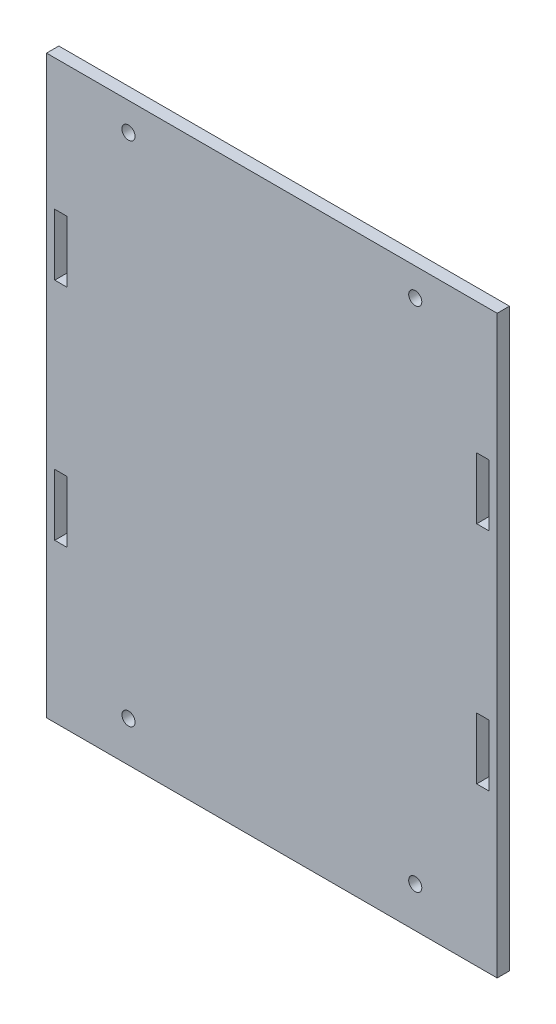
SolidWorks part; units mm, degrees
ref_plane "前视基准面" through (0, 0, 0) normal (0, 0, 1) x (1, 0, 0)
ref_plane "上视基准面" through (0, 0, 0) normal (0, 1, 0) x (1, 0, 0)
ref_plane "右视基准面" through (0, 0, 0) normal (1, 0, 0) x (0, 0, -1)
sketch "草图1" plane through (0, 0, 0) normal (0, 0, 1) x (1, 0, 0)
  line L0 (50, 124.6667) -> (50, -15.8667) construction
  line L1 (50, -15.8667) -> (178, -84.1333) construction
  line L2 (178, -84.1333) -> (294.7059, -5.8431) construction
  line L3 (294.7059, -5.8431) -> (50, 124.6667) construction
  line L4 (177.0588, -84.7647) -> (50, -17) construction
  line L5 (191.1765, -75.2941) -> (50, 0) construction
  line L6 (172.3529, 59.4118) -> (114, -50) construction
  line L7 (50, 124.6667) -> (-50, 124.6667)
  line L8 (50, -15.8667) -> (-50, -15.8667)
  line L9 (-50, -15.8667) -> (-50, 124.6667)
  line L10 (50, 124.6667) -> (50, -15.8667)
  line L11 (50, 0) -> (-50, 0) construction
  line L12 (-35, -6) -> (35, -6) construction
  line L13 (0, -6) -> (0, 0) construction
  line L14 (-35, 117.8667) -> (-50, 117.8667) construction
  line L15 (35, 117.8667) -> (50, 117.8667) construction
  circle A0 centre (-35, -6) radius 1.6
  circle A1 centre (35, -6) radius 1.6
  circle A2 centre (-35, 117.8667) radius 1.6
  circle A3 centre (35, 117.8667) radius 1.6
  point P9 (0, 0)
  dimension "D7" = 3.2
  dimension "D10" = 3.2
  dimension "D1" = 160
  dimension "D2" = 144
  dimension "D3" = 15
  dimension "D4" = 110
  dimension "D5" = 14
  dimension "D6" = 100
  dimension "D8" = 6
  dimension "D9" = 70
  dimension "D11" = 15
  dimension "D12" = 6
extrude "凸台-拉伸1" add sketch "草图1" against normal blind 3
sketch "草图2" plane through (0, 0, 0) normal (0, 0, 1) x (1, 0, 0)
  line L0 (-50, 124.6667) -> (-55, 124.6667)
  line L1 (-55, 124.6667) -> (-55, -15.8667)
  line L2 (-55, -15.8667) -> (-50, -15.8667)
  line L3 (-50, -15.8667) -> (-50, 124.6667)
  line L4 (-50, 92.6667) -> (-53, 92.6667)
  line L5 (-53, 92.6667) -> (-53, 77.6667)
  line L6 (-53, 77.6667) -> (-50, 77.6667)
  line L7 (-50, 92.6667) -> (-50, 77.6667)
  line L8 (-50, 37.6667) -> (-53, 37.6667)
  line L9 (-53, 37.6667) -> (-53, 22.6667)
  line L10 (-53, 22.6667) -> (-50, 22.6667)
  line L11 (-50, 22.6667) -> (-50, 37.6667)
  line M17 (-50, 124.6667) -> (-50, -15.8667)
  dimension "D1" = 32
  dimension "D2" = 15
  dimension "D3" = 40
  dimension "D4" = 3
  dimension "D5" = 2
extrude "凸台-拉伸2" add sketch "草图2" against normal up to surface (3 mm away) contours L10 L9 L8 L6 L5 L4 L0 L1 L2 M17 up to face at (36.6, 117.8667, -3)
mirror "镜向1" about plane through (0, 0, 0) normal (1, 0, 0) of "凸台-拉伸2"
